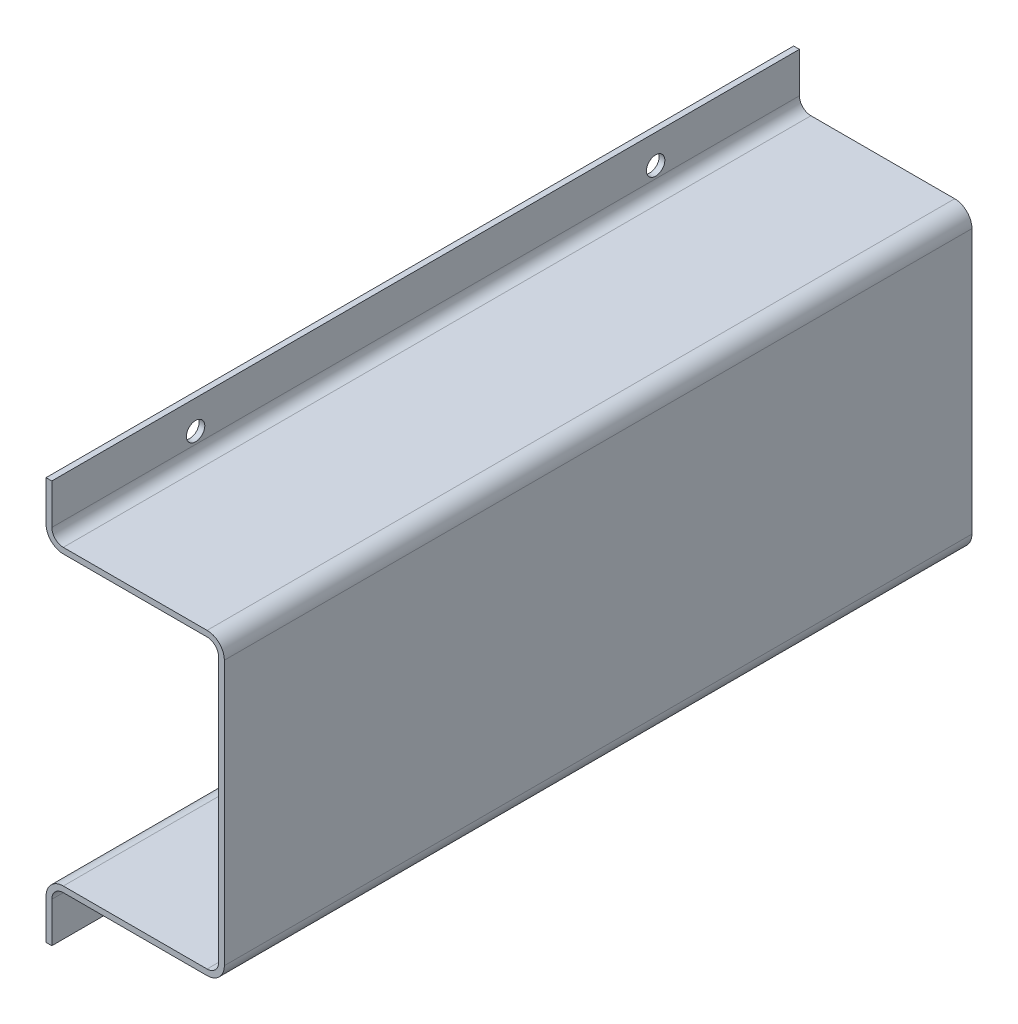
SolidWorks part; units mm, degrees
material "5052-O"
ref_plane "正面" through (0, 0, 0) normal (0, 0, 1) x (1, 0, 0)
ref_plane "平面" through (0, 0, 0) normal (0, 1, 0) x (1, 0, 0)
ref_plane "右側面" through (0, 0, 0) normal (1, 0, 0) x (0, 0, -1)
sketch "ｽｹｯﾁ1" plane through (0, 0, 0) normal (0, 0, 1) x (1, 0, 0)
  line L0 (0, 35) -> (0, 28)
  line L1 (3, 25) -> (28, 25)
  line L2 (30, 23) -> (30, 0)
  line L3 (1, 35) -> (1, 28)
  line L4 (3, 26) -> (28, 26)
  line L5 (31, 23) -> (31, 0)
  line L6 (0, 35) -> (1, 35)
  line L7 (30, 0) -> (31, 0)
  arc A0 (28, 25) -> (30, 23) centre (28, 23) cw
  arc A1 (0, 28) -> (3, 25) centre (3, 28) ccw
  arc A2 (1, 28) -> (3, 26) centre (3, 28) ccw
  arc A3 (28, 26) -> (31, 23) centre (28, 23) cw
  point P12 (30, 25)
  point P17 (0, 25)
  dimension "D5" = 2
  dimension "D6" = 3
  dimension "D1" = 25
  dimension "D2" = 30
  dimension "D3" = 10
  dimension "D4" = 1
extrude "ﾎﾞｽ - 押し出し1" add sketch "ｽｹｯﾁ1" along normal blind 130
sketch "ｽｹｯﾁ4" plane through (1, 0, 0) normal (1, 0, 0) x (0, 0, -1)
  line L1 (0, 0) -> (-130, 0) construction
  line L2 (-65, 0) -> (-65, 30) construction
  line L3 (-130, 0) -> (0, 0) construction
  line L4 (-105, 30) -> (-25, 30) construction
  dimension "D1" = 80
  dimension "D2" = 30
hole_wizard "M3 すきま穴2" positions "3Dｽｹｯﾁ2" profile "ｽｹｯﾁ5" hole size "M3" standard "JIS"
sketch3d "3Dｽｹｯﾁ2"
  point P0 (1, 30, 25)
  point P3 (1, 30, 105)
sketch "ｽｹｯﾁ5" plane through (1, 30, 25) normal (0, 1, 0) x (0, 0, -1)
  line L0 (0, 0) -> (0, 10.9614)
  line L1 (0, 10.9614) -> (1.6, 10)
  line L2 (1.6, 10) -> (1.6, 0)
  line L5 (1.6, 0) -> (0, 0)
  line L10 (0, 10.9614) -> (-1.6, 10) construction
  line L11 (0, -6.35) -> (0, 107.95) construction
  dimension "穴の直径" = 3.2
  dimension "穴の深さ" = 10
  dimension "ﾄﾞﾘﾙ角度" = 118
mirror "ﾐﾗｰ2" about plane through (0, 0, 0) normal (0, 1, 0) of "M3 すきま穴2", "ﾎﾞｽ - 押し出し1"
